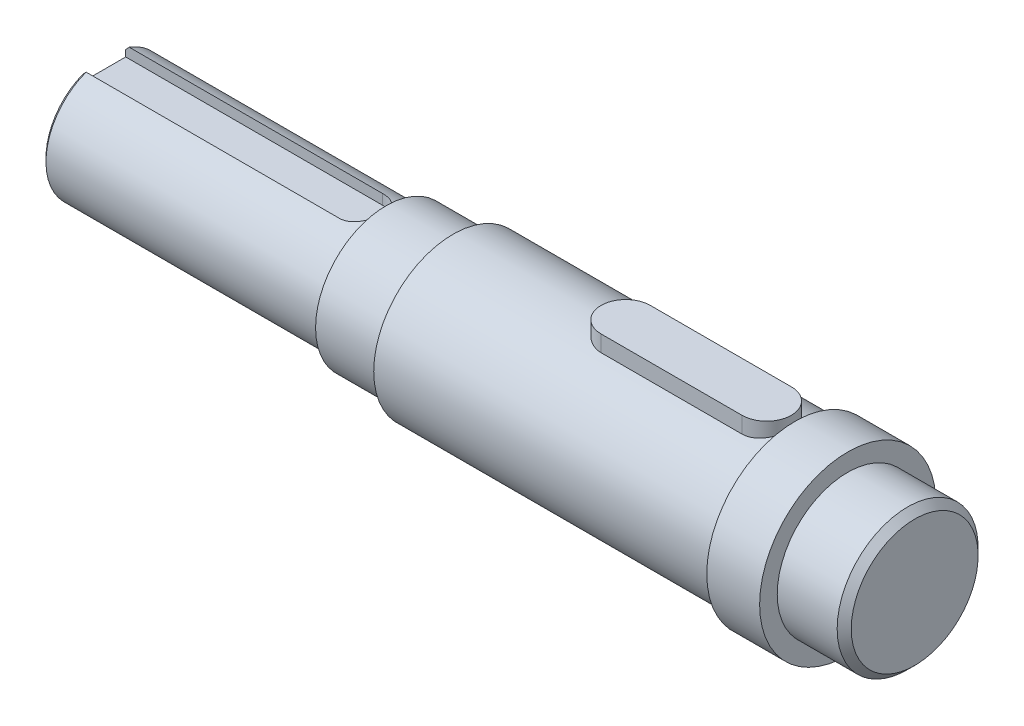
SolidWorks part; units mm, degrees
material "Alloy Steel"
ref_plane "Front Plane" through (0, 0, 0) normal (0, 0, 1) x (1, 0, 0)
ref_plane "Top Plane" through (0, 0, 0) normal (0, 1, 0) x (1, 0, 0)
ref_plane "Right Plane" through (0, 0, 0) normal (1, 0, 0) x (0, 0, -1)
sketch "Sketch1" plane through (0, 0, 0) normal (0, 0, 1) x (1, 0, 0)
  line L0 (-82.3203, 0) -> (423.8864, 0) construction
  line L1 (-63.5042, 0) -> (-63.5042, 17.5)
  line L2 (-63.5042, 17.5) -> (16.4958, 17.5)
  line L3 (16.4958, 17.5) -> (16.4958, 20)
  line L4 (16.4958, 20) -> (35.4958, 20)
  line L5 (35.4958, 20) -> (35.4958, 22.5)
  line L6 (35.4958, 22.5) -> (132.4958, 22.5)
  line L7 (147.4958, 25) -> (147.4958, 20)
  line L8 (147.4958, 20) -> (166.4958, 20)
  line L9 (166.4958, 20) -> (166.4958, 0)
  line L10 (-63.5042, 0) -> (166.4958, 0)
  line L11 (132.4958, 22.5) -> (132.4958, 25)
  line L12 (132.4958, 25) -> (147.4958, 25)
  dimension "D1" = 35
  dimension "D2" = 40
  dimension "D3" = 45
  dimension "D4" = 40
  dimension "D5" = 80
  dimension "D6" = 19
  dimension "D7" = 50
  dimension "D8" = 19
  dimension "D9" = 97
  dimension "D10" = 15
revolve "Revolve1" add sketch "Sketch1" angle 360 about L0
chamfer "Chamfer1" distance 1 angle 45 1 edges at (16.4958, 0, 17.5)
chamfer "Chamfer2" distance 1 angle 45 1 edges at (-63.5042, 0, 17.5)
chamfer "Chamfer3" distance 2 angle 45 1 edges at (166.4958, 0, 20)
sketch "Sketch2" plane through (0, 0, 0) normal (0, 1, 0) x (1, 0, 0)
  line L0 (-66.7927, 0) -> (9.3778, 0) construction
  line L2 (-66.7927, 6.118) -> (9.3778, 6.118)
  line L3 (-66.7927, -6.118) -> (9.3778, -6.118)
  line L4 (15.4958, 17.5) -> (15.4958, -17.5) construction
  arc A0 (-66.7927, 6.118) -> (-66.7927, -6.118) centre (-66.7927, 0) ccw
  arc A1 (9.3778, -6.118) -> (9.3778, 6.118) centre (9.3778, 0) ccw
  point P5 (-28.7075, 0)
extrude "Cut-Extrude1" cut sketch "Sketch2" against normal blind 4 from offset 17.5
sketch "Sketch3" plane through (0, 0, 0) normal (0, 1, 0) x (1, 0, 0)
  line L0 (84.4958, 0) -> (124.4958, 0) construction
  line L1 (84.4958, 7) -> (124.4958, 7)
  line L2 (84.4958, -7) -> (124.4958, -7)
  line L4 (132.4958, 22.5) -> (132.4958, -22.5) construction
  arc A0 (84.4958, 7) -> (84.4958, -7) centre (84.4958, 0) ccw
  arc A1 (124.4958, -7) -> (124.4958, 7) centre (124.4958, 0) ccw
  point P3 (104.4958, 0)
  dimension "D2" = 40
  dimension "D3" = 8
  dimension "D1" = 14
extrude "Cut-Extrude2" cut sketch "Sketch3" against normal blind 5.5 from offset 22.5
sketch "Sketch4" plane through (0, 17, 0) normal (0, 1, 0) x (1, 0, 0)
  line L2 (84.4958, -7) -> (124.4958, -7)
  line L3 (124.4958, 7) -> (84.4958, 7)
  line L4 (84.4958, -7) -> (124.4958, -7)
  line L5 (124.4958, 7) -> (84.4958, 7)
  arc A2 (84.4958, 7) -> (84.4958, -7) centre (84.4958, 0) ccw
  arc A3 (124.4958, -7) -> (124.4958, 7) centre (124.4958, 0) ccw
  arc A4 (84.4958, 7) -> (84.4958, -7) centre (84.4958, 0) ccw
  arc A5 (124.4958, -7) -> (124.4958, 7) centre (124.4958, 0) ccw
  dimension "D1" = 0
extrude "Boss-Extrude1" add sketch "Sketch4" along normal blind 9 separate body
